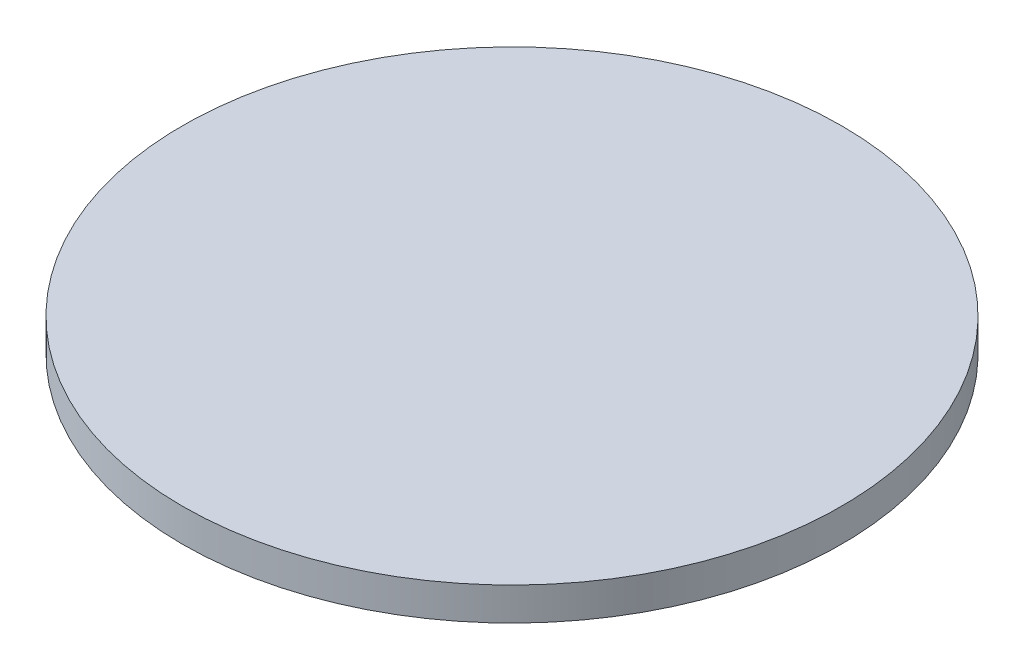
SolidWorks part; units mm, degrees
ref_plane "Front Plane" through (0, 0, 0) normal (0, 0, 1) x (1, 0, 0)
ref_plane "Top Plane" through (0, 0, 0) normal (0, 1, 0) x (1, 0, 0)
ref_plane "Right Plane" through (0, 0, 0) normal (1, 0, 0) x (0, 0, -1)
sketch "Sketch1" plane through (0, 0, 0) normal (0, 1, 0) x (1, 0, 0)
  circle A0 centre (0, 0) radius 50.8
extrude "Boss-Extrude1" add sketch "Sketch1" along normal blind 5.08
